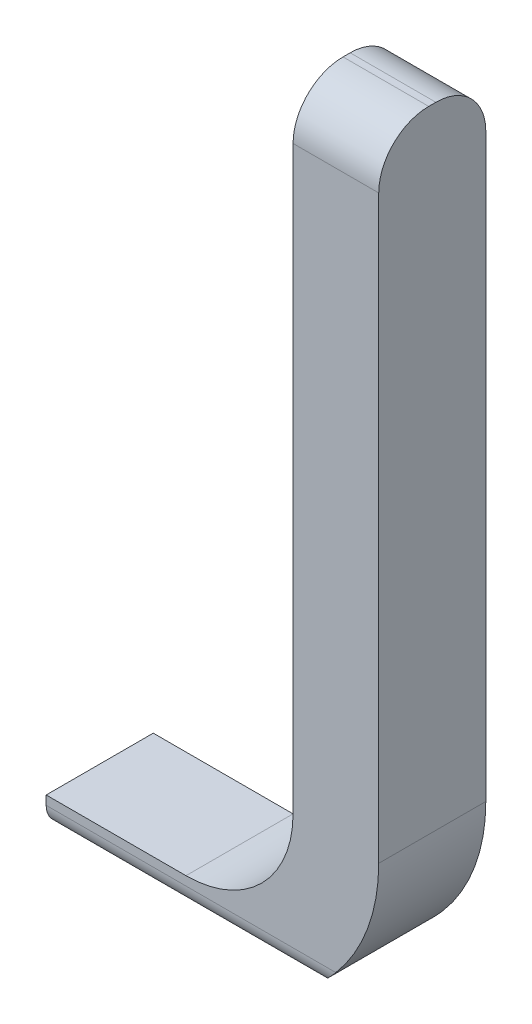
SolidWorks part; units mm, degrees
ref_plane "Front Plane" through (0, 0, 0) normal (0, 0, 1) x (1, 0, 0)
ref_plane "Top Plane" through (0, 0, 0) normal (0, 1, 0) x (1, 0, 0)
ref_plane "Right Plane" through (0, 0, 0) normal (1, 0, 0) x (0, 0, -1)
sketch "Sketch1" plane through (0, 0, 0) normal (0, 0, 1) x (1, 0, 0)
  line L0 (81.8142, 422.2536) -> (101.3962, 422.2536)
  line L1 (116.3962, 437.2536) -> (116.3962, 525.5762)
  line L2 (116.3962, 525.5762) -> (128.3962, 525.5762)
  line L3 (128.3962, 525.5762) -> (128.3962, 437.2536)
  line L4 (103.3962, 412.2536) -> (81.8142, 412.2536)
  line L7 (81.8142, 422.2536) -> (81.8142, 412.2536)
  arc A1 (101.3962, 422.2536) -> (116.3962, 437.2536) centre (101.3962, 437.2536) ccw
  arc A2 (103.3962, 412.2536) -> (128.3962, 437.2536) centre (103.3962, 437.2536) ccw
  point P2 (128.3962, 412.2536)
  point P3 (128.3962, 412.7385)
extrude "Boss-Extrude1" add sketch "Sketch1" against normal up to surface (15 mm away)
fillet "Fillet1" radius 7 2 edges at (122.3962, 525.5762, -15) (122.3962, 525.5762, 0)
sketch "Sketch2" plane through (128.3962, 0, 0) normal (1, 0, 0) x (0, 0, -1)
  line L0 (15, 422.2536) -> (0, 422.2536) construction
  line L1 (15, 422.2536) -> (0, 422.2536) construction
  line L2 (0, 419.7536) -> (7.5, 412.2536)
  line L3 (0, 437.2536) -> (0, 412.2536) construction
  line L4 (15, 412.2536) -> (0, 412.2536) construction
  line L5 (7.5, 412.2536) -> (15, 419.7536)
  line L6 (15, 412.2536) -> (15, 437.2536) construction
  line L7 (0, 419.7536) -> (0, 408.6913)
  line L8 (0, 408.6913) -> (15, 408.6913)
  line L9 (15, 408.6913) -> (15, 419.7536)
extrude "Cut-Extrude1" cut sketch "Sketch2" against normal up to surface (46.5819 mm away) up to face at (81.8142, 417.2536, -7.5)
fillet "Fillet2" radius 3 2 edges at (101.532, 419.7536, -15) (101.532, 419.7536, 0)
